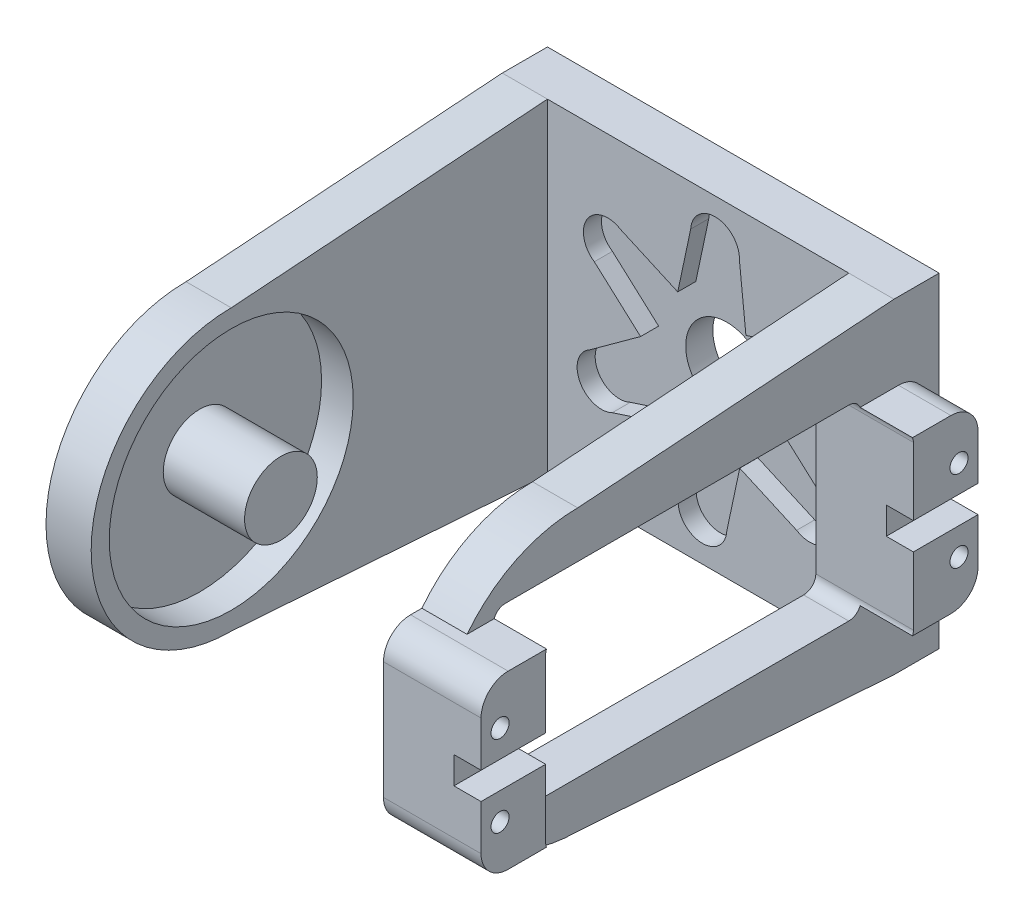
SolidWorks part; units mm, degrees
material "ABS"
ref_plane "Alzado" through (0, 0, 0) normal (0, 0, 1) x (1, 0, 0)
ref_plane "Planta" through (0, 0, 0) normal (0, 1, 0) x (1, 0, 0)
ref_plane "Vista lateral" through (0, 0, 0) normal (1, 0, 0) x (0, 0, -1)
sketch "Croquis1" plane through (-28.9731, 0, 0) normal (-1, 0, 0) x (0, 0, 1)
  line L0 (143.89, 8.3982) -> (143.89, -22.6018) construction
  line L1 (108.89, 10.8982) -> (108.89, -25.1018)
  line L2 (167.3689, -7.1018) -> (115.5329, -7.1018) construction
  line L3 (108.89, -25.1018) -> (143.89, -22.6018)
  line L4 (108.89, 10.8982) -> (143.89, 8.3982)
  arc A0 (143.89, -22.6018) -> (143.89, 8.3982) centre (143.89, -7.1018) ccw
  point P7 (108.89, -7.1018)
  dimension "D1" = 31
  dimension "D2" = 36
  dimension "D3" = 35
extrude "Saliente-Extruir1" add sketch "Croquis1" against normal blind 5 from offset 2.5
sketch "Croquis2" plane through (-26.4731, 0, 0) normal (1, 0, 0) x (0, 0, -1)
  circle A0 centre (-143.89, -7.1018) radius 13.5
  dimension "D1" = 27
extrude "Cortar-Extruir1" cut sketch "Croquis2" against normal offset from surface (3.5 mm away) 1.5 up to face at (-31.4731, -7.1018, 130.265)
sketch "Croquis4" plane through (-29.9731, 0, 0) normal (1, 0, 0) x (0, 0, -1)
  circle A0 centre (-143.89, -7.1018) radius 4.15 construction
  circle A1 centre (-143.89, -7.1018) radius 4.025
  dimension "D1" = 8.3
  dimension "D2" = 0.125
extrude "Saliente-Extruir3" add sketch "Croquis4" along normal blind 9
sketch "Croquis5" plane through (-31.4731, 0, 0) normal (-1, 0, 0) x (0, 0, 1)
  line L0 (108.89, 10.8982) -> (108.89, -25.1018) construction
  line L1 (108.89, 10.8982) -> (103.89, 10.8982)
  line L2 (108.89, 10.8982) -> (108.89, -25.1018)
  line L3 (108.89, -25.1018) -> (103.89, -25.1018)
  line L4 (103.89, 10.8982) -> (103.89, -25.1018)
  dimension "D1" = 5
extrude "Saliente-Extruir4" add sketch "Croquis5" against normal offset from surface (38.35 mm away) 2.5
sketch "Croquis6" plane through (0, 0, 108.89) normal (0, 0, 1) x (1, 0, 0)
  line L0 (-21.5597, -11.0559) -> (-15.6135, -6.7355) construction
  line L1 (-19.4259, -15.2436) -> (-12.4356, -12.9725) construction
  line L2 (-11.6671, -20.2822) -> (-12.4356, -12.9725) construction
  line L3 (-6.9735, -20.5282) -> (-5.4452, -13.3389) construction
  line L4 (1.2695, -16.3282) -> (-5.4452, -13.3389) construction
  line L5 (3.8293, -12.3864) -> (-1.6327, -7.4682) construction
  line L6 (4.3134, -3.1478) -> (-1.6327, -7.4682) construction
  line L7 (2.1797, 1.0399) -> (-4.8107, -1.2311) construction
  line L8 (-5.5791, 6.0786) -> (-4.8107, -1.2311) construction
  line L9 (-10.2727, 6.3246) -> (-11.8011, -0.8648) construction
  line L10 (-21.0755, -1.8172) -> (-15.6135, -6.7355) construction
  line L11 (-18.5157, 2.1245) -> (-11.8011, -0.8648) construction
  line L12 (-21.5597, -11.0559) -> (-15.6135, -6.7355) construction
  line L13 (-19.4259, -15.2436) -> (-12.4356, -12.9725) construction
  line L14 (-11.6671, -20.2822) -> (-12.4356, -12.9725) construction
  line L15 (-6.9735, -20.5282) -> (-5.4452, -13.3389) construction
  line L16 (1.2695, -16.3282) -> (-5.4452, -13.3389) construction
  line L17 (3.8293, -12.3864) -> (-1.6327, -7.4682) construction
  line L18 (4.3134, -3.1478) -> (-1.6327, -7.4682) construction
  line L19 (2.1797, 1.0399) -> (-4.8107, -1.2311) construction
  line L20 (-5.5791, 6.0786) -> (-4.8107, -1.2311) construction
  line L21 (-10.2727, 6.3246) -> (-11.8011, -0.8648) construction
  line L22 (-21.0755, -1.8172) -> (-15.6135, -6.7355) construction
  line L23 (-18.5157, 2.1245) -> (-11.8011, -0.8648) construction
  line L24 (-21.7439, -10.7571) -> (-16.1689, -6.7064)
  line L25 (-21.29, -2.0951) -> (-16.1689, -6.7064)
  line L26 (-18.3491, 2.4335) -> (-12.0535, -0.3693)
  line L27 (-10.6206, 6.3713) -> (-12.0535, -0.3693)
  line L28 (-5.2283, 6.0887) -> (-4.5078, -0.7647)
  line L29 (2.0462, 1.3646) -> (-4.5078, -0.7647)
  line L30 (4.4977, -3.4466) -> (-1.0773, -7.4973)
  line L31 (4.0437, -12.1086) -> (-1.0773, -7.4973)
  line L32 (1.1028, -16.6371) -> (-5.1927, -13.8344)
  line L33 (-6.6257, -20.575) -> (-5.1927, -13.8344)
  line L34 (-12.018, -20.2924) -> (-12.7385, -13.4389)
  line L35 (-19.2925, -15.5683) -> (-12.7385, -13.4389)
  arc A0 (-21.5597, -11.0559) -> (-19.4259, -15.2436) centre (-20.4928, -13.1497) ccw construction
  arc A1 (-11.6671, -20.2822) -> (-6.9735, -20.5282) centre (-9.3203, -20.4052) ccw construction
  arc A2 (1.2695, -16.3282) -> (3.8293, -12.3864) centre (2.5494, -14.3573) ccw construction
  arc A3 (4.3134, -3.1478) -> (2.1797, 1.0399) centre (3.2466, -1.0539) ccw construction
  arc A4 (-5.5791, 6.0786) -> (-10.2727, 6.3246) centre (-7.9259, 6.2016) ccw construction
  arc A5 (-18.5157, 2.1245) -> (-21.0755, -1.8172) centre (-19.7956, 0.1537) ccw construction
  arc A6 (-21.5597, -11.0559) -> (-19.4259, -15.2436) centre (-20.4928, -13.1497) ccw construction
  arc A7 (-11.6671, -20.2822) -> (-6.9735, -20.5282) centre (-9.3203, -20.4052) ccw construction
  arc A8 (1.2695, -16.3282) -> (3.8293, -12.3864) centre (2.5494, -14.3573) ccw construction
  arc A9 (4.3134, -3.1478) -> (2.1797, 1.0399) centre (3.2466, -1.0539) ccw construction
  arc A10 (-5.5791, 6.0786) -> (-10.2727, 6.3246) centre (-7.9259, 6.2016) ccw construction
  arc A11 (-18.5157, 2.1245) -> (-21.0755, -1.8172) centre (-19.7956, 0.1537) ccw construction
  arc A12 (-18.3491, 2.4335) -> (-21.29, -2.0951) centre (-19.7956, 0.1537) ccw
  arc A13 (-5.2283, 6.0887) -> (-10.6206, 6.3713) centre (-7.9259, 6.2016) ccw
  arc A14 (4.4977, -3.4466) -> (2.0462, 1.3646) centre (3.2466, -1.0539) ccw
  arc A15 (1.1028, -16.6371) -> (4.0437, -12.1086) centre (2.5494, -14.3573) ccw
  arc A16 (-12.018, -20.2924) -> (-6.6257, -20.575) centre (-9.3203, -20.4052) ccw
  arc A17 (-21.7439, -10.7571) -> (-19.2925, -15.5683) centre (-20.4928, -13.1497) ccw
  dimension "D1" = 0.35
extrude "Cortar-Extruir2" cut sketch "Croquis6" against normal blind 2
sketch "Croquis8" plane through (0, 0, 106.89) normal (0, 0, 1) x (1, 0, 0)
  circle A0 centre (-8.6231, -7.1018) radius 4.2 construction
  circle A1 centre (-8.6231, -7.1018) radius 4.2 construction
  circle A2 centre (-8.6231, -7.1018) radius 4.55
  dimension "D1" = 0.35
extrude "Cortar-Extruir3" cut sketch "Croquis8" against normal through all
sketch "Croquis9" plane through (6.8769, 0, 0) normal (1, 0, 0) x (0, 0, -1)
  line L3 (-143.89, -22.6018) -> (-108.89, -25.1018)
  line L4 (-108.89, -25.1018) -> (-108.89, 10.8982)
  line L5 (-108.89, 10.8982) -> (-143.89, 8.3982)
  line L6 (-143.89, -22.6018) -> (-108.89, -25.1018)
  line L8 (-108.89, 10.8982) -> (-143.89, 8.3982)
  line L11 (-108.89, 10.8982) -> (-108.89, -25.1018)
  line L12 (-108.89, -25.1018) -> (-103.89, -25.1018)
  line L13 (-103.89, -25.1018) -> (-103.89, 10.8982)
  line L14 (-103.89, 10.8982) -> (-108.89, 10.8982)
  line L16 (-108.89, -25.1018) -> (-103.89, -25.1018)
  line L17 (-103.89, -25.1018) -> (-103.89, 10.8982)
  line L18 (-103.89, 10.8982) -> (-108.89, 10.8982)
  arc A1 (-143.89, 8.3982) -> (-143.89, -22.6018) centre (-143.89, -7.1018) ccw
  arc A2 (-143.89, 8.3982) -> (-143.89, -22.6018) centre (-143.89, -7.1018) ccw
  dimension "D1" = 0
  dimension "D2" = 0
extrude "Saliente-Extruir5" add sketch "Croquis9" along normal blind 5
sketch "Croquis11" plane through (11.8769, 0, 0) normal (1, 0, 0) x (0, 0, -1)
  line L8 (-153.24, 1.8982) -> (-153.24, -16.1018)
  line L9 (-151.89, -17.4518) -> (-113.89, -17.4518)
  line L10 (-112.54, -16.1018) -> (-112.54, 1.8982)
  line L11 (-113.89, 3.2482) -> (-151.89, 3.2482)
  line L12 (-153.24, 1.8982) -> (-153.24, -16.1018)
  line L13 (-151.89, -17.4518) -> (-113.89, -17.4518)
  line L14 (-112.54, -16.1018) -> (-112.54, 1.8982)
  line L15 (-113.89, 3.2482) -> (-151.89, 3.2482)
  arc A8 (-153.24, -16.1018) -> (-151.89, -17.4518) centre (-151.89, -16.1018) ccw
  arc A9 (-113.89, -17.4518) -> (-112.54, -16.1018) centre (-113.89, -16.1018) ccw
  arc A10 (-112.54, 1.8982) -> (-113.89, 3.2482) centre (-113.89, 1.8982) ccw
  arc A11 (-151.89, 3.2482) -> (-153.24, 1.8982) centre (-151.89, 1.8982) ccw
  arc A12 (-153.24, -16.1018) -> (-151.89, -17.4518) centre (-151.89, -16.1018) ccw
  arc A13 (-113.89, -17.4518) -> (-112.54, -16.1018) centre (-113.89, -16.1018) ccw
  arc A14 (-112.54, 1.8982) -> (-113.89, 3.2482) centre (-113.89, 1.8982) ccw
  arc A15 (-151.89, 3.2482) -> (-153.24, 1.8982) centre (-151.89, 1.8982) ccw
  dimension "D1" = 0.35
extrude "Cortar-Extruir4" cut sketch "Croquis11" against normal up to surface (5 mm away) up to face at (6.8769, -7.1018, 130.265)
sketch "Croquis12" plane through (11.8769, 0, 0) normal (1, 0, 0) x (0, 0, -1)
  line L0 (-105.39, -1.2518) -> (-105.39, -3.9518)
  line L1 (-105.39, -10.2518) -> (-105.39, -12.9518)
  line L2 (-112.54, -16.1018) -> (-112.54, 1.8982) construction
  line L3 (-112.54, -16.1018) -> (-112.54, 1.8982)
  line L10 (-112.89, -6.1018) -> (-106.89, -6.1018)
  line L11 (-112.89, 1.8982) -> (-112.89, -6.1018)
  line L12 (-108.39, 2.3982) -> (-113.024, 2.3982)
  line L13 (-105.39, -1.2518) -> (-105.39, -0.6018)
  line L14 (-105.39, -10.2518) -> (-105.39, -3.9518)
  line L15 (-105.39, -13.6018) -> (-105.39, -12.9518)
  line L16 (-113.024, -16.6018) -> (-108.39, -16.6018)
  line L17 (-112.89, -8.1018) -> (-112.89, -16.1018)
  line L18 (-106.89, -8.1018) -> (-112.89, -8.1018)
  line L19 (-106.89, -6.1018) -> (-106.89, -8.1018)
  line L22 (-108.39, 2.3982) -> (-112.636, 2.3982)
  line L23 (-105.39, -1.2518) -> (-105.39, -0.6018)
  line L24 (-105.39, -10.2518) -> (-105.39, -3.9518)
  line L25 (-105.39, -13.6018) -> (-105.39, -12.9518)
  line L26 (-112.636, -16.6018) -> (-108.39, -16.6018)
  circle A0 centre (-107.4942, -2.6018) radius 1
  circle A1 centre (-107.4942, -11.6018) radius 1
  arc A2 (-113.89, -17.4518) -> (-112.54, -16.1018) centre (-113.89, -16.1018) ccw construction
  arc A3 (-112.54, 1.8982) -> (-113.89, 3.2482) centre (-113.89, 1.8982) ccw construction
  arc A4 (-112.636, -16.6018) -> (-112.54, -16.1018) centre (-113.89, -16.1018) ccw
  arc A5 (-112.54, 1.8982) -> (-112.636, 2.3982) centre (-113.89, 1.8982) ccw
  arc A6 (-112.89, 1.8982) -> (-113.024, 2.3982) centre (-113.89, 1.8982) ccw
  arc A7 (-105.39, -0.6018) -> (-108.39, 2.3982) centre (-108.39, -0.6018) ccw
  arc A8 (-105.39, -1.2518) -> (-105.39, -3.9518) centre (-107.4942, -2.6018) ccw
  arc A9 (-105.39, -10.2518) -> (-105.39, -12.9518) centre (-107.4942, -11.6018) ccw
  arc A10 (-108.39, -16.6018) -> (-105.39, -13.6018) centre (-108.39, -13.6018) ccw
  arc A11 (-113.024, -16.6018) -> (-112.89, -16.1018) centre (-113.89, -16.1018) ccw
  arc A13 (-105.39, -0.6018) -> (-108.39, 2.3982) centre (-108.39, -0.6018) ccw
  arc A16 (-108.39, -16.6018) -> (-105.39, -13.6018) centre (-108.39, -13.6018) ccw
  dimension "D2" = 2
  dimension "D1" = 0
extrude "Saliente-Extruir6" add sketch "Croquis12" along normal offset from surface (3.65 mm away) 0.35
sketch "Croquis13" plane through (6.8769, 0, 0) normal (-1, 0, 0) x (0, 0, 1)
  line L0 (153.24, -16.1018) -> (153.24, 1.8982) construction
  line L1 (153.24, -16.1018) -> (153.24, 1.8982)
  line L2 (160.39, -1.2518) -> (160.39, -3.9518)
  line L3 (160.39, -12.9518) -> (160.39, -10.2518)
  line L10 (158.89, -8.1018) -> (152.89, -8.1018)
  line L11 (152.89, -8.1018) -> (152.89, -16.1018)
  line L12 (152.756, -16.6018) -> (157.39, -16.6018)
  line L13 (160.39, -13.6018) -> (160.39, -12.9518)
  line L14 (160.39, -10.2518) -> (160.39, -3.9518)
  line L15 (160.39, -1.2518) -> (160.39, -0.6018)
  line L16 (157.39, 2.3982) -> (152.756, 2.3982)
  line L17 (152.89, 1.8982) -> (152.89, -6.1018)
  line L18 (152.89, -6.1018) -> (158.89, -6.1018)
  line L19 (158.89, -6.1018) -> (158.89, -8.1018)
  line L22 (153.144, -16.6018) -> (157.39, -16.6018)
  line L23 (160.39, -13.6018) -> (160.39, -12.9518)
  line L24 (160.39, -10.2518) -> (160.39, -3.9518)
  line L25 (160.39, -1.2518) -> (160.39, -0.6018)
  line L26 (157.39, 2.3982) -> (153.144, 2.3982)
  arc A0 (151.89, -17.4518) -> (153.24, -16.1018) centre (151.89, -16.1018) ccw construction
  arc A1 (153.24, 1.8982) -> (151.89, 3.2482) centre (151.89, 1.8982) ccw construction
  arc A2 (153.144, -16.6018) -> (153.24, -16.1018) centre (151.89, -16.1018) ccw
  arc A3 (153.24, 1.8982) -> (153.144, 2.3982) centre (151.89, 1.8982) ccw
  arc A6 (152.756, -16.6018) -> (152.89, -16.1018) centre (151.89, -16.1018) ccw
  arc A7 (157.39, -16.6018) -> (160.39, -13.6018) centre (157.39, -13.6018) ccw
  arc A8 (160.39, -10.2518) -> (160.39, -12.9518) centre (158.2858, -11.6018) ccw
  arc A9 (160.39, -1.2518) -> (160.39, -3.9518) centre (158.2858, -2.6018) ccw
  arc A10 (160.39, -0.6018) -> (157.39, 2.3982) centre (157.39, -0.6018) ccw
  arc A11 (152.89, 1.8982) -> (152.756, 2.3982) centre (151.89, 1.8982) ccw
  arc A13 (157.39, -16.6018) -> (160.39, -13.6018) centre (157.39, -13.6018) ccw
  arc A16 (160.39, -0.6018) -> (157.39, 2.3982) centre (157.39, -0.6018) ccw
  dimension "D1" = 0
extrude "Saliente-Extruir7" add sketch "Croquis13" against normal offset from surface (8.65 mm away) 0.35
sketch "Croquis14" plane through (15.5269, 0, 0) normal (1, 0, 0) x (0, 0, -1)
  circle A0 centre (-158.2858, -2.6018) radius 1
  circle A1 centre (-158.2858, -11.6018) radius 1
  dimension "D1" = 2
  dimension "D2" = 2
extrude "Cortar-Extruir5" cut sketch "Croquis14" against normal up to surface (3.65 mm away) up to face at (11.8769, -2.6018, 106.4942)
sketch "Croquis15" plane through (15.5269, 0, 0) normal (1, 0, 0) x (0, 0, -1)
  line L0 (-112.54, 1.8982) -> (-112.54, -16.1018) construction
  line L1 (-105.39, -5.9268) -> (-112.54, -5.9268)
  line L2 (-105.39, -5.9268) -> (-105.39, -8.2768)
  line L3 (-105.39, -8.2768) -> (-112.54, -8.2768)
  line L4 (-112.54, -5.9268) -> (-112.54, -8.2768)
  line L6 (-153.24, 1.8982) -> (-153.24, -16.1018) construction
  line L7 (-160.39, -5.9268) -> (-153.24, -5.9268)
  line L8 (-160.39, -5.9268) -> (-160.39, -8.2768)
  line L9 (-160.39, -8.2768) -> (-153.24, -8.2768)
  line L10 (-153.24, -5.9268) -> (-153.24, -8.2768)
  line L12 (-160.39, -13.6018) -> (-160.39, -0.6018) construction
  line L13 (-105.39, -13.6018) -> (-105.39, -0.6018) construction
  point P7 (-112.54, -7.1018)
  point P8 (-112.54, -7.1018)
  point P16 (-160.39, -7.1018)
  point P17 (-160.39, -7.1018)
  dimension "D1" = 2.35
  dimension "D2" = 2.35
extrude "Cortar-Extruir6" cut sketch "Croquis15" against normal offset from surface (2 mm away) 0.35
sketch "Croquis16" plane through (13.5269, 0, 0) normal (1, 0, 0) x (0, 0, -1)
  line L4 (-160.39, -5.9268) -> (-160.39, -8.2768)
  line L5 (-160.39, -8.2768) -> (-153.24, -8.2768)
  line L6 (-153.24, -8.2768) -> (-153.24, -5.9268)
  line L7 (-153.24, -5.9268) -> (-160.39, -5.9268)
  line L8 (-160.39, -5.9268) -> (-160.39, -8.2768)
  line L9 (-160.39, -8.2768) -> (-153.24, -8.2768)
  line L10 (-153.24, -8.2768) -> (-153.24, -5.9268)
  line L11 (-153.24, -5.9268) -> (-160.39, -5.9268)
  line L12 (-105.39, -8.2768) -> (-105.39, -5.9268)
  line L13 (-105.39, -5.9268) -> (-112.54, -5.9268)
  line L14 (-112.54, -5.9268) -> (-112.54, -8.2768)
  line L15 (-112.54, -8.2768) -> (-105.39, -8.2768)
  line L16 (-105.39, -8.2768) -> (-105.39, -5.9268)
  line L17 (-105.39, -5.9268) -> (-112.54, -5.9268)
  line L18 (-112.54, -5.9268) -> (-112.54, -8.2768)
  line L19 (-112.54, -8.2768) -> (-105.39, -8.2768)
  dimension "D1" = 0
  dimension "D2" = 0
extrude "Saliente-Extruir8" add sketch "Croquis16" along normal up to surface (2 mm away) up to face at (15.5269, -0.8558, 109.3735)
sketch "Croquis17" plane through (15.5269, 0, 0) normal (1, 0, 0) x (0, 0, -1)
  line L4 (-105.39, -13.6018) -> (-105.39, -0.6018)
  line L5 (-108.39, 2.3982) -> (-112.636, 2.3982)
  line L6 (-112.54, 1.8982) -> (-112.54, -16.1018)
  line L7 (-112.636, -16.6018) -> (-108.39, -16.6018)
  line L8 (-105.39, -13.6018) -> (-105.39, -0.6018)
  line L9 (-108.39, 2.3982) -> (-112.636, 2.3982)
  line L10 (-112.54, 1.8982) -> (-112.54, -16.1018)
  line L11 (-112.636, -16.6018) -> (-108.39, -16.6018)
  line L12 (-160.39, -0.6018) -> (-160.39, -13.6018)
  line L13 (-157.39, -16.6018) -> (-153.144, -16.6018)
  line L14 (-153.24, -16.1018) -> (-153.24, 1.8982)
  line L15 (-153.144, 2.3982) -> (-157.39, 2.3982)
  line L16 (-160.39, -0.6018) -> (-160.39, -13.6018)
  line L17 (-157.39, -16.6018) -> (-153.144, -16.6018)
  line L18 (-153.24, -16.1018) -> (-153.24, 1.8982)
  line L19 (-153.144, 2.3982) -> (-157.39, 2.3982)
  circle A0 centre (-158.2858, -11.6018) radius 1 construction
  circle A1 centre (-158.2858, -2.6018) radius 1 construction
  circle A2 centre (-158.2858, -11.6018) radius 1
  circle A3 centre (-158.2858, -2.6018) radius 1
  arc A4 (-105.39, -0.6018) -> (-108.39, 2.3982) centre (-108.39, -0.6018) ccw
  arc A5 (-112.54, 1.8982) -> (-112.636, 2.3982) centre (-113.89, 1.8982) ccw
  arc A6 (-112.636, -16.6018) -> (-112.54, -16.1018) centre (-113.89, -16.1018) ccw
  arc A7 (-108.39, -16.6018) -> (-105.39, -13.6018) centre (-108.39, -13.6018) ccw
  arc A8 (-105.39, -0.6018) -> (-108.39, 2.3982) centre (-108.39, -0.6018) ccw
  arc A9 (-112.54, 1.8982) -> (-112.636, 2.3982) centre (-113.89, 1.8982) ccw
  arc A10 (-112.636, -16.6018) -> (-112.54, -16.1018) centre (-113.89, -16.1018) ccw
  arc A11 (-108.39, -16.6018) -> (-105.39, -13.6018) centre (-108.39, -13.6018) ccw
  arc A12 (-157.39, 2.3982) -> (-160.39, -0.6018) centre (-157.39, -0.6018) ccw
  arc A13 (-160.39, -13.6018) -> (-157.39, -16.6018) centre (-157.39, -13.6018) ccw
  arc A14 (-153.24, -16.1018) -> (-153.144, -16.6018) centre (-151.89, -16.1018) ccw
  arc A15 (-153.144, 2.3982) -> (-153.24, 1.8982) centre (-151.89, 1.8982) ccw
  arc A16 (-157.39, 2.3982) -> (-160.39, -0.6018) centre (-157.39, -0.6018) ccw
  arc A17 (-160.39, -13.6018) -> (-157.39, -16.6018) centre (-157.39, -13.6018) ccw
  arc A18 (-153.24, -16.1018) -> (-153.144, -16.6018) centre (-151.89, -16.1018) ccw
  arc A19 (-153.144, 2.3982) -> (-153.24, 1.8982) centre (-151.89, 1.8982) ccw
  circle A20 centre (-107.4942, -11.6018) radius 1 construction
  circle A21 centre (-107.4942, -2.6018) radius 1 construction
  circle A22 centre (-107.4942, -11.6018) radius 1
  circle A23 centre (-107.4942, -2.6018) radius 1
  dimension "D1" = 0
  dimension "D2" = 0
extrude "Saliente-Extruir9" add sketch "Croquis17" along normal blind 2.15
sketch "Croquis18" plane through (17.6769, 0, 0) normal (1, 0, 0) x (0, 0, -1)
  line L0 (-160.39, -0.6018) -> (-160.39, -13.6018) construction
  line L1 (-160.39, -5.6018) -> (-105.39, -5.6018)
  line L2 (-160.39, -5.6018) -> (-160.39, -8.6018)
  line L3 (-160.39, -8.6018) -> (-105.39, -8.6018)
  line L4 (-105.39, -5.6018) -> (-105.39, -8.6018)
  line L5 (-105.39, -13.6018) -> (-105.39, -0.6018) construction
  point P8 (-160.39, -7.1018)
  point P9 (-160.39, -7.1018)
  dimension "D1" = 3
extrude "Cortar-Extruir7" cut sketch "Croquis18" against normal blind 3
